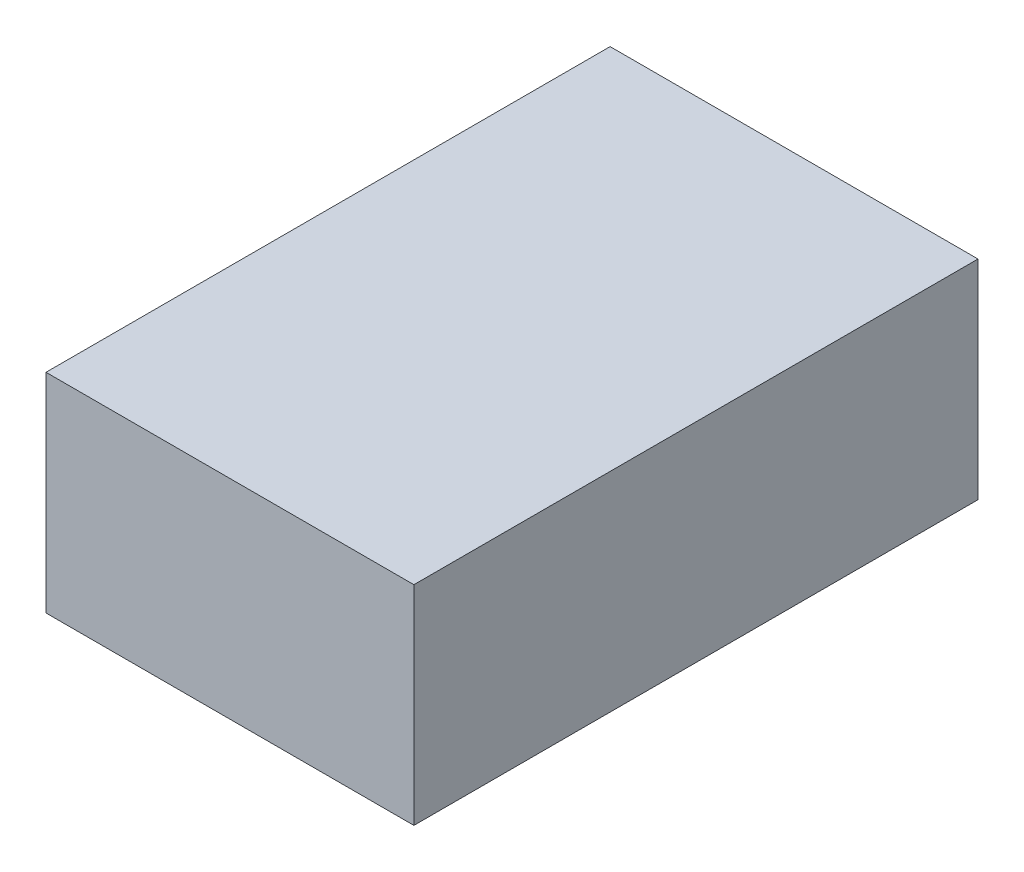
SolidWorks part; units mm, degrees
material "1023 Carbon Steel Sheet (SS)"
ref_plane "Front Plane" through (0, 0, 0) normal (0, 0, 1) x (1, 0, 0)
ref_plane "Top Plane" through (0, 0, 0) normal (0, 1, 0) x (1, 0, 0)
ref_plane "Right Plane" through (0, 0, 0) normal (1, 0, 0) x (0, 0, -1)
sketch "Sketch1" plane through (0, 0, 0) normal (0, 1, 0) x (1, 0, 0)
  line L1 (-1532.2535, 1431.831) -> (-1232.2535, 1431.831)
  line L2 (-1532.2535, 1431.831) -> (-1532.2535, 971.831)
  line L3 (-1532.2535, 971.831) -> (-1232.2535, 971.831)
  line L4 (-1232.2535, 1431.831) -> (-1232.2535, 971.831)
  dimension "D1" = 460
  dimension "D2" = 300
extrude "Accumulator" add sketch "Sketch1" along normal blind 170
